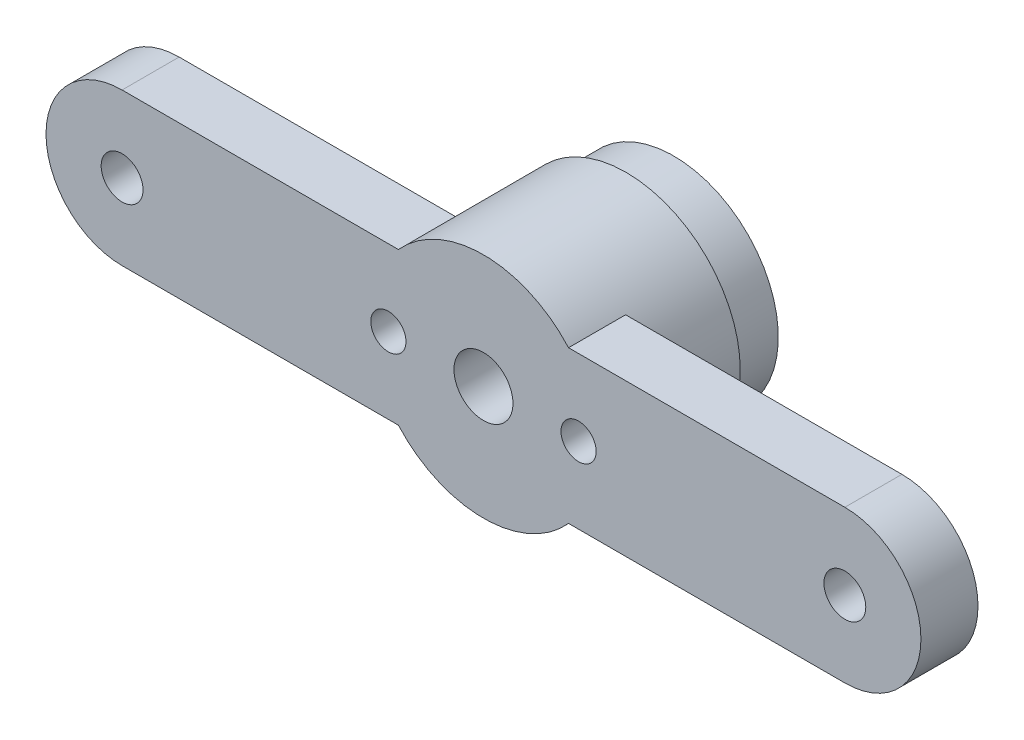
SolidWorks part; units mm, degrees
ref_plane "前视基准面" through (0, 0, 0) normal (0, 0, 1) x (1, 0, 0)
ref_plane "上视基准面" through (0, 0, 0) normal (0, 1, 0) x (1, 0, 0)
ref_plane "右视基准面" through (0, 0, 0) normal (1, 0, 0) x (0, 0, -1)
sketch "草图1" plane through (0, 0, 0) normal (0, 0, 1) x (1, 0, 0)
  line L0 (4.4721, 4) -> (19, 4)
  line L1 (-19, -4) -> (-4.4721, -4)
  line L2 (4.4721, -4) -> (19, -4)
  line L3 (-19, 4) -> (-4.4721, 4)
  circle A0 centre (0, 0) radius 1.55
  circle A1 centre (19, 0) radius 1.1
  circle A2 centre (-19, 0) radius 1.1
  arc A3 (-19, 4) -> (-19, -4) centre (-19, 0) ccw
  arc A4 (19, -4) -> (19, 4) centre (19, 0) ccw
  arc A5 (-4.4721, -4) -> (4.4721, -4) centre (0, 0) ccw
  arc A6 (4.4721, 4) -> (-4.4721, 4) centre (0, 0) ccw
  dimension "D3" = 2.2
  dimension "D4" = 2.2
  dimension "D5" = 3.1
  dimension "D7" = 8
  dimension "D9" = 4
  dimension "D6" = 8
  dimension "D1" = 19
  dimension "D2" = 19
  dimension "D10" = 4
extrude "凸台-拉伸1" add sketch "草图1" along normal blind 3
sketch "草图2" plane through (0, 0, 0) normal (0, 0, -1) x (-1, 0, 0)
  circle A0 centre (0, 0) radius 6
extrude "凸台-拉伸2" add sketch "草图2" along normal blind 4.5
sketch "草图3" plane through (0, 0, -4.5) normal (0, 0, -1) x (-1, 0, 0)
  circle A0 centre (0, 0) radius 5.5
  dimension "D1" = 11
extrude "凸台-拉伸3" add sketch "草图3" along normal blind 2.5
sketch "草图4" plane through (0, 0, -7) normal (0, 0, -1) x (-1, 0, 0)
  circle A0 centre (0, 0) radius 2.6
  dimension "D1" = 5.2
sketch "草图5" plane through (0, 0, -7) normal (0, 0, -1) x (-1, 0, 0)
  circle A0 centre (0, 2.6) radius 0.4
  circle A1 centre (0, 0) radius 2.6 construction
  dimension "D1" = 0.8
extrude "切除-拉伸1" cut sketch "草图5" against normal blind 5
pattern_circular "阵列(圆周)2" count 25 over 360 about axis through (0, 0, 0) along (0, 0, 1) of "切除-拉伸1"
extrude "切除-拉伸2" cut sketch "草图4" against normal blind 5
sketch "草图6" plane through (0, 0, 3) normal (0, 0, 1) x (1, 0, 0)
  circle A0 centre (0, 0) radius 1.55
extrude "切除-拉伸3" cut sketch "草图6" against normal blind 30
sketch "草图7" plane through (0, 0, 3) normal (0, 0, 1) x (1, 0, 0)
  circle A0 centre (5, 0) radius 0.925
  circle A1 centre (-5, 0) radius 0.925
  dimension "D3" = 1.85
  dimension "D4" = 1.85
  dimension "D1" = 5
  dimension "D2" = 5
extrude "切除-拉伸4" cut sketch "草图7" against normal blind 6
ref_plane "基准面1" through (6, 0, 0) normal (1, 0, 0) x (0, 0, -1)
sketch "草图8" plane through (6, 0, 0) normal (1, 0, 0) x (0, 0, -1)
  line L0 (1.6, 2.1) -> (0, 2.1)
  line L1 (1.6, 2.1) -> (1.6, -2.1)
  line L2 (0, 2.1) -> (0, -2.1)
  line L3 (1.6, -2.1) -> (0, -2.1)
  line L4 (1.6, 2.1) -> (0, -2.1) construction
  line L5 (0, 2.1) -> (1.6, -2.1) construction
  point P1 (0.8, 0)
  dimension "D1" = 4.2
  dimension "D2" = 1.6
extrude "切除-拉伸5" cut sketch "草图8" against normal blind 3.2
ref_plane "基准面2" through (-6, 0, 0) normal (-1, 0, 0) x (0, 0, 1)
sketch "草图9" plane through (-6, 0, 0) normal (-1, 0, 0) x (0, 0, 1)
  line L0 (-1.6, -2.1) -> (0, -2.1)
  line L1 (-1.6, -2.1) -> (-1.6, 2.1)
  line L2 (0, -2.1) -> (0, 2.1)
  line L3 (-1.6, 2.1) -> (0, 2.1)
  line L4 (-1.6, -2.1) -> (0, 2.1) construction
  line L5 (0, -2.1) -> (-1.6, 2.1) construction
  point P1 (-0.8, 0)
  dimension "D1" = 1.6
  dimension "D2" = 4.2
extrude "切除-拉伸6" cut sketch "草图9" against normal blind 3.2
